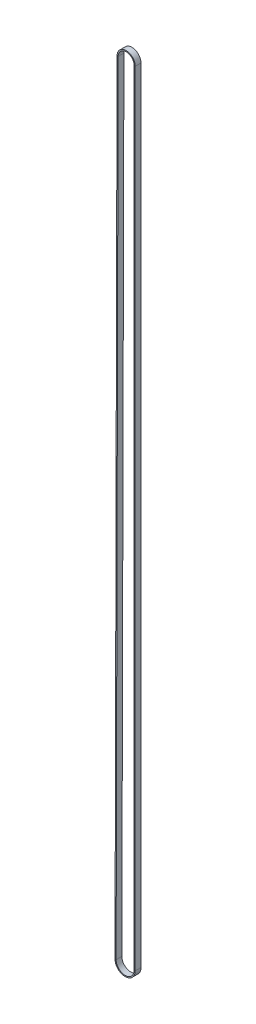
SolidWorks part; units mm, degrees
ref_plane "Płaszczyzna przednia" through (0, 0, 0) normal (0, 0, 1) x (1, 0, 0)
ref_plane "Płaszczyzna górna" through (0, 0, 0) normal (0, 1, 0) x (1, 0, 0)
ref_plane "Płaszczyzna prawa" through (0, 0, 0) normal (1, 0, 0) x (0, 0, -1)
sketch "Szkic1" plane through (0, 0, 0) normal (0, 0, 1) x (1, 0, 0)
  line L0 (70.4983, -96.6527) -> (70.4983, 721.3466)
  line L1 (69.3483, -96.6527) -> (69.3483, 721.3466)
  line L2 (50.5083, -96.628) -> (52.6483, 721.3685)
  line L3 (49.3583, -96.625) -> (51.4983, 721.3715)
  arc A0 (70.4983, 721.3466) -> (51.4983, 721.3715) centre (60.9983, 721.3466) ccw
  arc A1 (70.4983, -96.6527) -> (49.3583, -96.625) centre (59.9283, -96.6527) cw
  arc A2 (69.3483, 721.3466) -> (52.6483, 721.3685) centre (60.9983, 721.3466) ccw
  arc A3 (69.3483, -96.6527) -> (50.5083, -96.628) centre (59.9283, -96.6527) cw
  dimension "D3" = 10.57
  dimension "D4" = 1.15
  dimension "D1" = 818
  dimension "D2" = 9.5
extrude "Dodanie-wyciągnięcie1" add sketch "Szkic1" along normal blind 6
